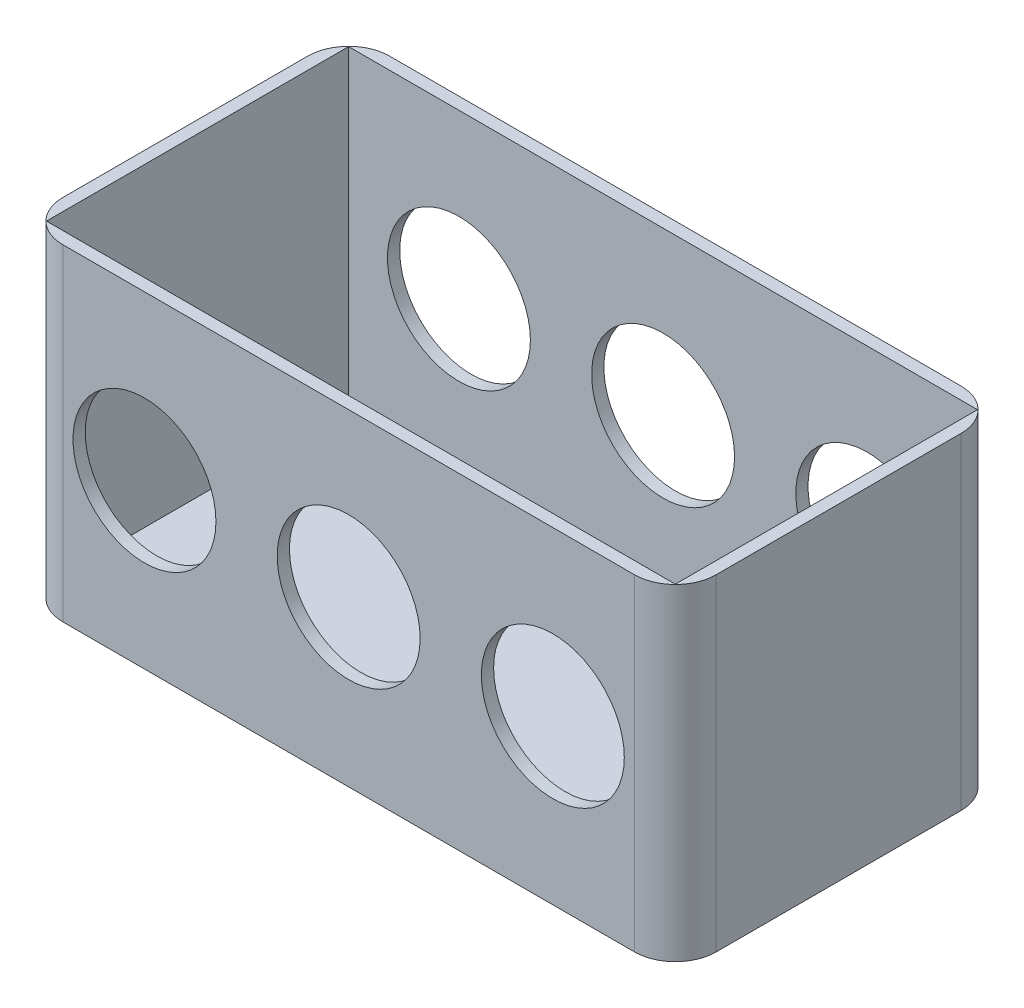
SolidWorks part; units mm, degrees
ref_plane "Front Plane" through (0, 0, 0) normal (0, 0, 1) x (1, 0, 0)
ref_plane "Top Plane" through (0, 0, 0) normal (0, 1, 0) x (1, 0, 0)
ref_plane "Right Plane" through (0, 0, 0) normal (1, 0, 0) x (0, 0, -1)
sketch "Sketch1" plane through (0, 0, 0) normal (0, 1, 0) x (1, 0, 0)
  line L0 (-90.2088, 0) -> (99.3039, 0) construction
  line L1 (0, 57.0766) -> (0, -59.8608) construction
  line L3 (-80, 40) -> (80, 40)
  line L4 (-80, 40) -> (-80, -40)
  line L5 (-80, -40) -> (80, -40)
  line L6 (80, 40) -> (80, -40)
  line L7 (-80, 40) -> (80, -40) construction
  line L8 (-80, -40) -> (80, 40) construction
  point P5 (0, 0)
  dimension "D1" = 80
  dimension "D2" = 160
extrude "Boss-Extrude1" add sketch "Sketch1" along normal blind 80
shell "Shell1" thickness 3
sketch "Sketch2" plane through (0, 0, 40) normal (0, 0, 1) x (1, 0, 0)
  line L0 (0, -22.4891) -> (0, 102.9992) construction
  line L1 (-103.2133, 40) -> (126.3385, 40) construction
  line L2 (-80, 0) -> (80, 0) construction
  circle A0 centre (-50, 40) radius 17.5
  circle A1 centre (0, 40.2551) radius 17.5
  circle A2 centre (50, 40) radius 17.5
  dimension "D2" = 35
  dimension "D3" = 35
  dimension "D4" = 35
  dimension "D1" = 40
  dimension "D5" = 50
  dimension "D6" = 50
extrude "Cut-Extrude1" cut sketch "Sketch2" against normal blind 80
fillet "Fillet1" radius 10 4 edges at (-80, 40, 40) (80, 40, 40) (80, 40, -40) (-80, 40, -40)
